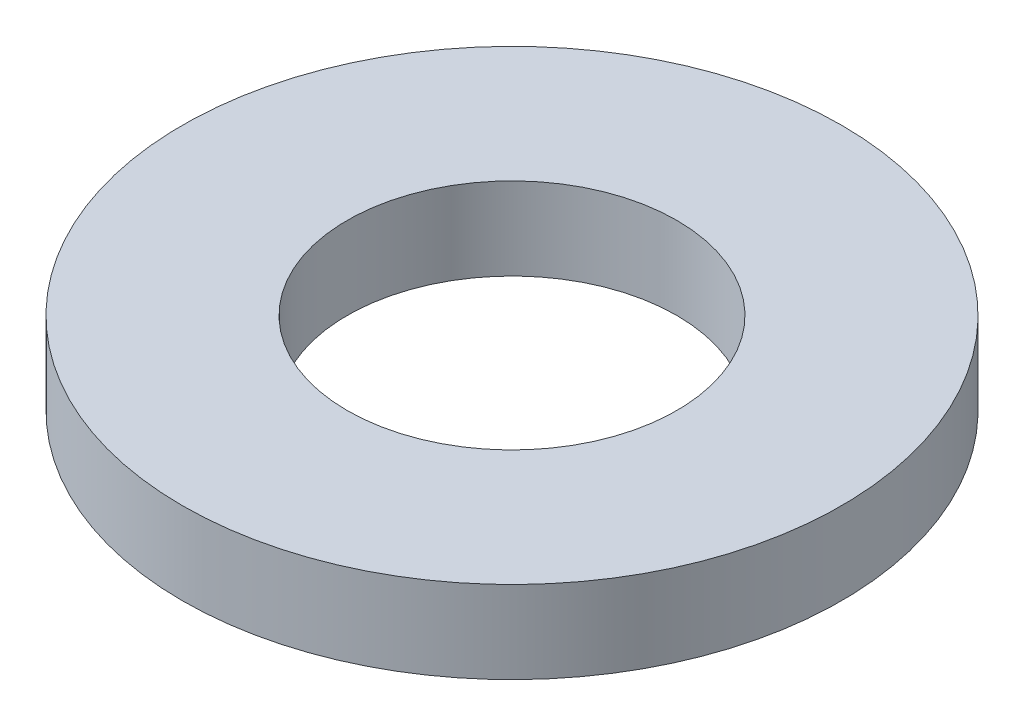
SolidWorks part; units mm, degrees
material "6061-O (SS)"
ref_plane "Ebene vorne" through (0, 0, 0) normal (0, 0, 1) x (1, 0, 0)
ref_plane "Ebene oben" through (0, 0, 0) normal (0, 1, 0) x (1, 0, 0)
ref_plane "Ebene rechts" through (0, 0, 0) normal (1, 0, 0) x (0, 0, -1)
sketch "Skizze1" plane through (0, 0, 0) normal (0, 0, 1) x (1, 0, 0)
  line L0 (8, 0) -> (8, 2)
  line L1 (8, 2) -> (4, 2)
  line L2 (4, 2) -> (4, 0)
  line L3 (4, 0) -> (8, 0)
  line L4 (0, 2) -> (0, 0) construction
revolve "Rotation1" add sketch "Skizze1" angle 360 about L4
